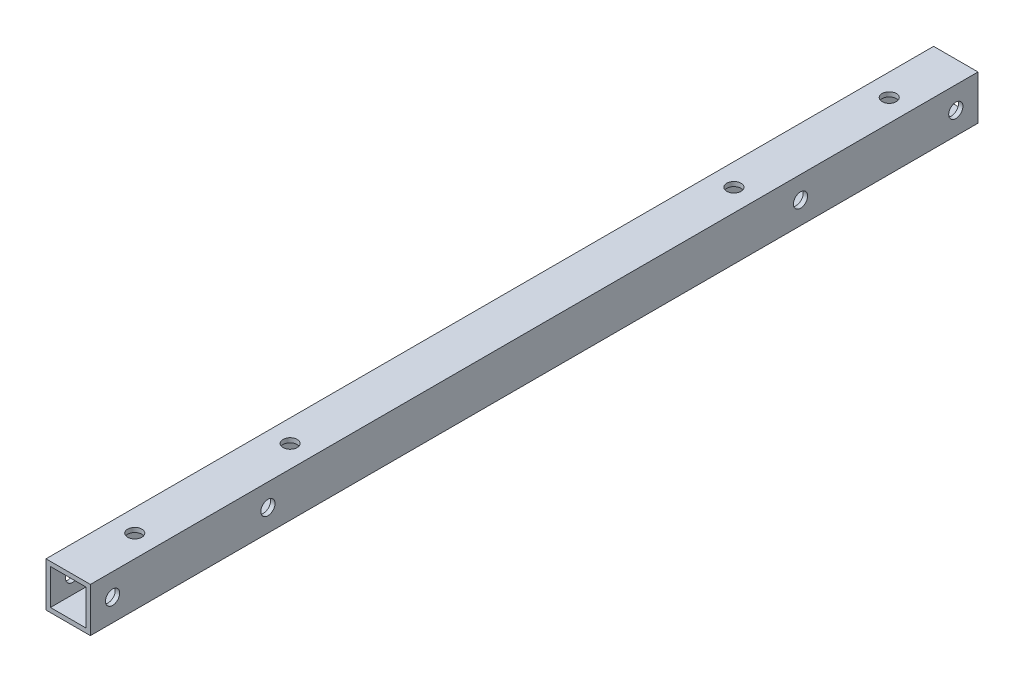
SolidWorks part; units mm, degrees
ref_plane "正面" through (0, 0, 0) normal (0, 0, 1) x (1, 0, 0)
ref_plane "平面" through (0, 0, 0) normal (0, 1, 0) x (1, 0, 0)
ref_plane "右側面" through (0, 0, 0) normal (1, 0, 0) x (0, 0, -1)
sketch "ｽｹｯﾁ1" plane through (0, 0, 0) normal (0, 0, 1) x (1, 0, 0)
  line L0 (-4, 4) -> (-4, -4)
  line L1 (-5, 5) -> (5, 5)
  line L2 (-5, 5) -> (-5, -5)
  line L3 (-5, -5) -> (5, -5)
  line L4 (5, 5) -> (5, -5)
  line L5 (-5, 5) -> (5, -5) construction
  line L6 (-5, -5) -> (5, 5) construction
  line L7 (-4, -4) -> (4, -4)
  line L8 (4, 4) -> (4, -4)
  line L9 (-4, 4) -> (4, 4)
  point P0 (0, 0)
  dimension "D1" = 10
  dimension "D2" = 10
  dimension "D3" = 1
extrude "ﾎﾞｽ - 押し出し1" add sketch "ｽｹｯﾁ1" along normal blind 200
sketch "ｽｹｯﾁ2" plane through (5, 0, 0) normal (1, 0, 0) x (0, 0, -1)
  line L0 (5.5, 0) -> (-5.5, 0) construction
  line L1 (-200, -5) -> (-200, 5) construction
  line L2 (0, 5.5) -> (0, -5.5) construction
  circle A0 centre (-160, 0) radius 1.6
  circle A1 centre (-40, 0) radius 1.6
  circle A2 centre (-195, 0) radius 1.6
  circle A3 centre (-5, 0) radius 1.6
  dimension "D1" = 3.2
  dimension "D2" = 3.2
  dimension "D3" = 40
  dimension "D4" = 40
  dimension "D5" = 3.2
  dimension "D6" = 5
  dimension "D7" = 3.2
  dimension "D8" = 5
extrude "ｶｯﾄ - 押し出し1" cut sketch "ｽｹｯﾁ2" against normal through all and the other way through all
sketch "ｽｹｯﾁ3" plane through (0, 5, 0) normal (0, 1, 0) x (1, 0, 0)
  line L0 (0, -5.5) -> (0, 5.5) construction
  line L1 (5, -200) -> (-5, -200) construction
  line L2 (-5.5, 0) -> (5.5, 0) construction
  circle A0 centre (0, -185) radius 1.6
  circle A1 centre (0, -15) radius 1.6
  dimension "D1" = 3.2
  dimension "D2" = 15
  dimension "D3" = 3.2
  dimension "D4" = 15
extrude "ｶｯﾄ - 押し出し2" cut sketch "ｽｹｯﾁ3" against normal through all
sketch "ｽｹｯﾁ4" plane through (0, 5, 0) normal (0, 1, 0) x (1, 0, 0)
  line L0 (0, -5.5) -> (0, 5.5) construction
  line L1 (-5.5, 0) -> (5.5, 0) construction
  line L2 (-4, -200) -> (4, -200) construction
  circle A0 centre (0, -50) radius 1.6
  circle A1 centre (0, -150) radius 1.6
  dimension "D1" = 3.2
  dimension "D2" = 50
  dimension "D3" = 3.2
  dimension "D4" = 50
extrude "ｶｯﾄ - 押し出し3" cut sketch "ｽｹｯﾁ4" against normal through all
